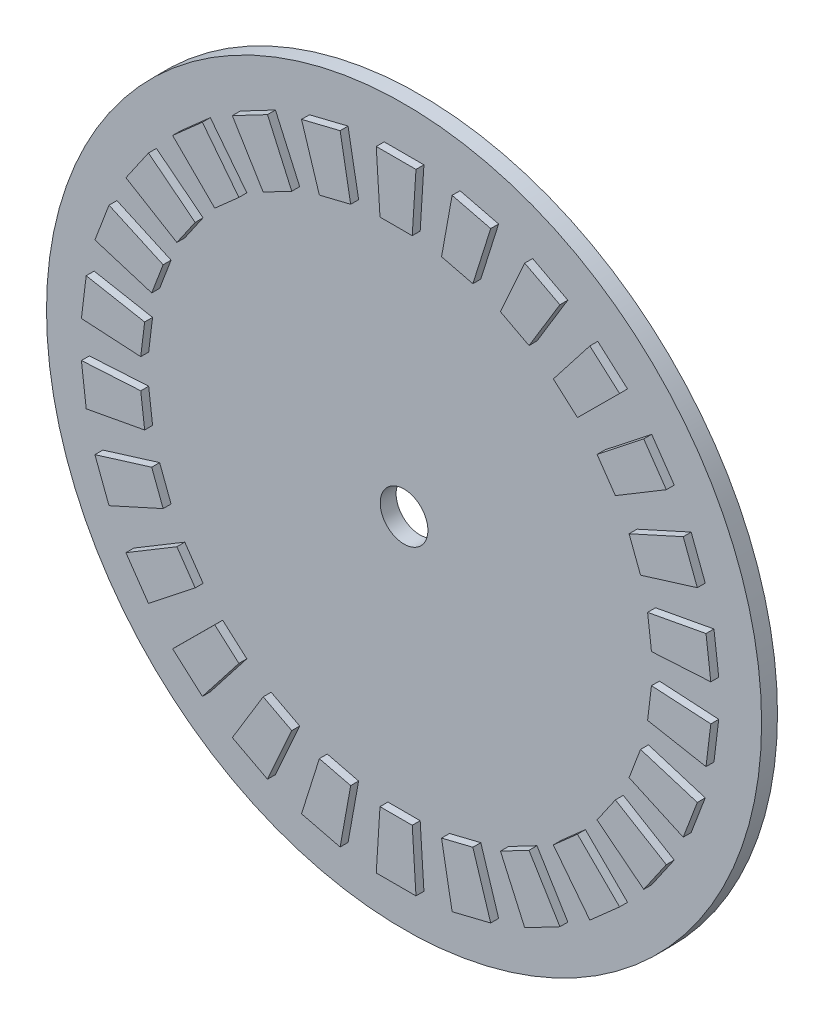
SolidWorks part; units mm, degrees
ref_plane "Front Plane" through (0, 0, 0) normal (0, 0, 1) x (1, 0, 0)
ref_plane "Top Plane" through (0, 0, 0) normal (0, 1, 0) x (1, 0, 0)
ref_plane "Right Plane" through (0, 0, 0) normal (1, 0, 0) x (0, 0, -1)
sketch "Sketch1" plane through (0, 0, 0) normal (0, 0, 1) x (1, 0, 0)
  circle A0 centre (0, 0) radius 45
  circle A1 centre (0, 0) radius 3
  dimension "D1" = 90
  dimension "D2" = 6
extrude "Boss-Extrude1" add sketch "Sketch1" along normal blind 2
sketch "Sketch2" plane through (0, 0, 2) normal (0, 0, 1) x (1, 0, 0)
  line L0 (0, 0) -> (0, 39.592) construction
  line L1 (-16.4182, 39.592) -> (12.2841, 39.592) construction
  line L2 (2.5, 39.592) -> (-2.5, 39.592)
  line L3 (-2.0287, 32.1285) -> (2.0287, 32.1285)
  line L4 (-2.5, 39.592) -> (-2.0287, 32.1285)
  line L5 (2.0287, 32.1285) -> (2.5, 39.592)
  line L6 (-2.5, 39.592) -> (0, 0) construction
  line L7 (11.9023, 37.8432) -> (7.0476, 39.0398)
  line L8 (5.7191, 31.6804) -> (9.6586, 30.7094)
  line L9 (7.0476, 39.0398) -> (5.7191, 31.6804)
  line L10 (9.6586, 30.7094) -> (11.9023, 37.8432)
  line L11 (20.613, 33.8952) -> (16.1857, 36.2188)
  line L12 (13.1345, 29.3912) -> (16.7272, 27.5056)
  line L13 (16.1857, 36.2188) -> (13.1345, 29.3912)
  line L14 (16.7272, 27.5056) -> (20.613, 33.8952)
  line L15 (28.1256, 27.9772) -> (24.3831, 31.2929)
  line L16 (19.7866, 25.3938) -> (22.8237, 22.7032)
  line L17 (24.3831, 31.2929) -> (19.7866, 25.3938)
  line L18 (22.8237, 22.7032) -> (28.1256, 27.9772)
  line L19 (34.0037, 20.4334) -> (31.1634, 24.5483)
  line L20 (25.2888, 19.9207) -> (27.5937, 16.5815)
  line L21 (31.1634, 24.5483) -> (25.2888, 19.9207)
  line L22 (27.5937, 16.5815) -> (34.0037, 20.4334)
  line L23 (37.9057, 11.702) -> (36.1327, 16.3771)
  line L24 (29.3213, 13.2898) -> (30.7601, 9.496)
  line L25 (36.1327, 16.3771) -> (29.3213, 13.2898)
  line L26 (30.7601, 9.496) -> (37.9057, 11.702)
  line L27 (39.6047, 2.2905) -> (39.002, 7.2541)
  line L28 (31.6497, 5.8866) -> (32.1388, 1.8587)
  line L29 (39.002, 7.2541) -> (31.6497, 5.8866)
  line L30 (32.1388, 1.8587) -> (39.6047, 2.2905)
  line L31 (39.002, -7.2541) -> (39.6047, -2.2905)
  line L32 (32.1388, -1.8587) -> (31.6497, -5.8866)
  line L33 (39.6047, -2.2905) -> (32.1388, -1.8587)
  line L34 (31.6497, -5.8866) -> (39.002, -7.2541)
  line L35 (36.1327, -16.3771) -> (37.9057, -11.702)
  line L36 (30.7601, -9.496) -> (29.3213, -13.2898)
  line L37 (37.9057, -11.702) -> (30.7601, -9.496)
  line L38 (29.3213, -13.2898) -> (36.1327, -16.3771)
  line L39 (31.1634, -24.5483) -> (34.0037, -20.4334)
  line L40 (27.5937, -16.5815) -> (25.2888, -19.9207)
  line L41 (34.0037, -20.4334) -> (27.5937, -16.5815)
  line L42 (25.2888, -19.9207) -> (31.1634, -24.5483)
  line L43 (24.3831, -31.2929) -> (28.1256, -27.9772)
  line L44 (22.8237, -22.7032) -> (19.7866, -25.3938)
  line L45 (28.1256, -27.9772) -> (22.8237, -22.7032)
  line L46 (19.7866, -25.3938) -> (24.3831, -31.2929)
  line L47 (16.1857, -36.2188) -> (20.613, -33.8952)
  line L48 (16.7272, -27.5056) -> (13.1345, -29.3912)
  line L49 (20.613, -33.8952) -> (16.7272, -27.5056)
  line L50 (13.1345, -29.3912) -> (16.1857, -36.2188)
  line L51 (7.0476, -39.0398) -> (11.9023, -37.8432)
  line L52 (9.6586, -30.7094) -> (5.7191, -31.6804)
  line L53 (11.9023, -37.8432) -> (9.6586, -30.7094)
  line L54 (5.7191, -31.6804) -> (7.0476, -39.0398)
  line L55 (-2.5, -39.592) -> (2.5, -39.592)
  line L56 (2.0287, -32.1285) -> (-2.0287, -32.1285)
  line L57 (2.5, -39.592) -> (2.0287, -32.1285)
  line L58 (-2.0287, -32.1285) -> (-2.5, -39.592)
  line L59 (-11.9023, -37.8432) -> (-7.0476, -39.0398)
  line L60 (-5.7191, -31.6804) -> (-9.6586, -30.7094)
  line L61 (-7.0476, -39.0398) -> (-5.7191, -31.6804)
  line L62 (-9.6586, -30.7094) -> (-11.9023, -37.8432)
  line L63 (-20.613, -33.8952) -> (-16.1857, -36.2188)
  line L64 (-13.1345, -29.3912) -> (-16.7272, -27.5056)
  line L65 (-16.1857, -36.2188) -> (-13.1345, -29.3912)
  line L66 (-16.7272, -27.5056) -> (-20.613, -33.8952)
  line L67 (-28.1256, -27.9772) -> (-24.3831, -31.2929)
  line L68 (-19.7866, -25.3938) -> (-22.8237, -22.7032)
  line L69 (-24.3831, -31.2929) -> (-19.7866, -25.3938)
  line L70 (-22.8237, -22.7032) -> (-28.1256, -27.9772)
  line L71 (-34.0037, -20.4334) -> (-31.1634, -24.5483)
  line L72 (-25.2888, -19.9207) -> (-27.5937, -16.5815)
  line L73 (-31.1634, -24.5483) -> (-25.2888, -19.9207)
  line L74 (-27.5937, -16.5815) -> (-34.0037, -20.4334)
  line L75 (-37.9057, -11.702) -> (-36.1327, -16.3771)
  line L76 (-29.3213, -13.2898) -> (-30.7601, -9.496)
  line L77 (-36.1327, -16.3771) -> (-29.3213, -13.2898)
  line L78 (-30.7601, -9.496) -> (-37.9057, -11.702)
  line L79 (-39.6047, -2.2905) -> (-39.002, -7.2541)
  line L80 (-31.6497, -5.8866) -> (-32.1388, -1.8587)
  line L81 (-39.002, -7.2541) -> (-31.6497, -5.8866)
  line L82 (-32.1388, -1.8587) -> (-39.6047, -2.2905)
  line L83 (-39.002, 7.2541) -> (-39.6047, 2.2905)
  line L84 (-32.1388, 1.8587) -> (-31.6497, 5.8866)
  line L85 (-39.6047, 2.2905) -> (-32.1388, 1.8587)
  line L86 (-31.6497, 5.8866) -> (-39.002, 7.2541)
  line L87 (-36.1327, 16.3771) -> (-37.9057, 11.702)
  line L88 (-30.7601, 9.496) -> (-29.3213, 13.2898)
  line L89 (-37.9057, 11.702) -> (-30.7601, 9.496)
  line L90 (-29.3213, 13.2898) -> (-36.1327, 16.3771)
  line L91 (-31.1634, 24.5483) -> (-34.0037, 20.4334)
  line L92 (-27.5937, 16.5815) -> (-25.2888, 19.9207)
  line L93 (-34.0037, 20.4334) -> (-27.5937, 16.5815)
  line L94 (-25.2888, 19.9207) -> (-31.1634, 24.5483)
  line L95 (-24.3831, 31.2929) -> (-28.1256, 27.9772)
  line L96 (-22.8237, 22.7032) -> (-19.7866, 25.3938)
  line L97 (-28.1256, 27.9772) -> (-22.8237, 22.7032)
  line L98 (-19.7866, 25.3938) -> (-24.3831, 31.2929)
  line L99 (-16.1857, 36.2188) -> (-20.613, 33.8952)
  line L100 (-16.7272, 27.5056) -> (-13.1345, 29.3912)
  line L101 (-20.613, 33.8952) -> (-16.7272, 27.5056)
  line L102 (-13.1345, 29.3912) -> (-16.1857, 36.2188)
  line L103 (-7.0476, 39.0398) -> (-11.9023, 37.8432)
  line L104 (-9.6586, 30.7094) -> (-5.7191, 31.6804)
  line L105 (-11.9023, 37.8432) -> (-9.6586, 30.7094)
  line L106 (-5.7191, 31.6804) -> (-7.0476, 39.0398)
  point P112 (0, 0)
  dimension "D1" = 5
  dimension "D2" = 26
extrude "Boss-Extrude2" add sketch "Sketch2" along normal blind 1
